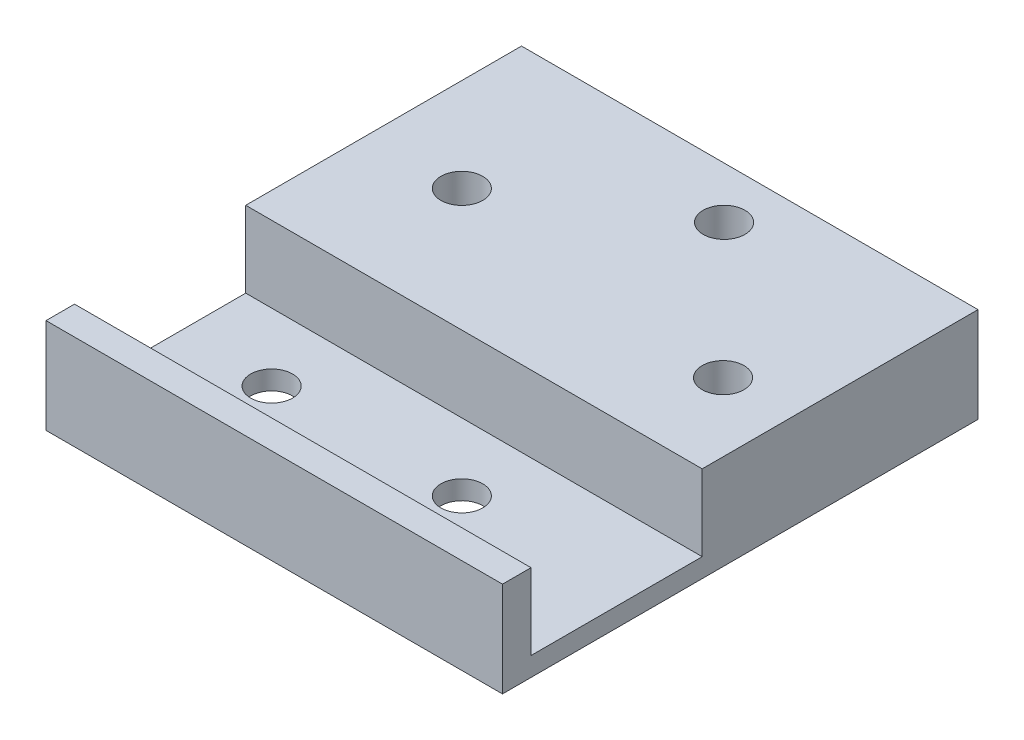
SolidWorks part; units mm, degrees
ref_plane "Front Plane" through (0, 0, 0) normal (0, 0, 1) x (1, 0, 0)
ref_plane "Top Plane" through (0, 0, 0) normal (0, 1, 0) x (1, 0, 0)
ref_plane "Right Plane" through (0, 0, 0) normal (1, 0, 0) x (0, 0, -1)
sketch "Sketch1" plane through (0, 0, 0) normal (0, 1, 0) x (1, 0, 0)
  line L1 (-60, -27.5) -> (60, -27.5)
  line L2 (-60, -27.5) -> (-60, 27.5)
  line L3 (-60, 27.5) -> (60, 27.5)
  line L4 (60, -27.5) -> (60, 27.5)
  line L5 (-60, -27.5) -> (60, 27.5) construction
  line L6 (-60, 27.5) -> (60, -27.5) construction
  point P0 (0, 0)
  dimension "D1" = 55
  dimension "D2" = 120
extrude "Boss-Extrude1" add sketch "Sketch1" along normal blind 5
sketch "Sketch2" plane through (0, 5, 0) normal (0, 1, 0) x (1, 0, 0)
  line L0 (60, -27.5) -> (60, 27.5) construction
  line L1 (-60, -27.5) -> (60, -27.5)
  line L2 (-60, -27.5) -> (-60, -20)
  line L3 (-60, -20) -> (60, -20)
  line L4 (60, -27.5) -> (60, -20)
  dimension "D1" = 7.5
extrude "Boss-Extrude2" add sketch "Sketch2" along normal blind 20
sketch "Sketch3" plane through (0, 5, 0) normal (0, 1, 0) x (1, 0, 0)
  line L0 (-60, 27.5) -> (-60, -20) construction
  line L1 (60, 27.5) -> (-60, 27.5)
  line L2 (60, 27.5) -> (60, 25)
  line L3 (60, 25) -> (-60, 25)
  line L4 (-60, 27.5) -> (-60, 25)
  dimension "D1" = 2.5
extrude "Boss-Extrude4" add sketch "Sketch3" along normal blind 20
sketch "Sketch8" plane through (-60, 0, 0) normal (-1, 0, 0) x (0, 0, 1)
  line L0 (-27.5, 0) -> (-27.5, 25)
  line L1 (-27.5, 25) -> (-25, 25)
  line L2 (-25, 25) -> (-25, 5)
  line L3 (-25, 5) -> (20, 5)
  line L4 (20, 5) -> (20, 25)
  line L5 (20, 25) -> (27.5, 25)
  line L6 (27.5, 25) -> (27.5, 0)
  line L7 (27.5, 0) -> (-27.5, 0)
extrude "Boss-Extrude5" add sketch "Sketch8" along normal blind 190
sketch "Sketch9" plane through (0, 0, -27.5) normal (0, 0, -1) x (-1, 0, 0)
  line L0 (-60, 0) -> (-60, 25)
  line L1 (-60, 25) -> (250, 25)
  line L2 (250, 25) -> (250, 0)
  line L3 (250, 0) -> (-60, 0)
extrude "Boss-Extrude6" add sketch "Sketch9" along normal blind 70
sketch "Sketch14" plane through (0, 0, 0) normal (0, -1, 0) x (-1, 0, 0)
  circle A0 centre (225.4453, 7.2552) radius 5.5
  circle A1 centre (175.4453, 7.2552) radius 5.5
  circle A2 centre (225.4453, 57.2552) radius 5.5
  circle A3 centre (148.0182, 48.5) radius 5.5
  circle A4 centre (183.2409, 83.9875) radius 5.5
  dimension "D1" = 11
  dimension "D3" = 11
  dimension "D5" = 11
  dimension "D6" = 11
  dimension "D8" = 11
  dimension "D2" = 50
  dimension "D4" = 50
  dimension "D7" = 50
extrude "Cut-Extrude5" cut sketch "Sketch14" against normal blind 153
sketch "Sketch15" plane through (60, 0, 0) normal (1, 0, 0) x (0, 0, -1)
  line L1 (-27.5, 25) -> (97.5, 25)
  line L2 (-27.5, 25) -> (-27.5, 0)
  line L3 (-27.5, 0) -> (97.5, 0)
  line L4 (97.5, 25) -> (97.5, 0)
extrude "Cut-Extrude6" cut sketch "Sketch15" against normal blind 190
